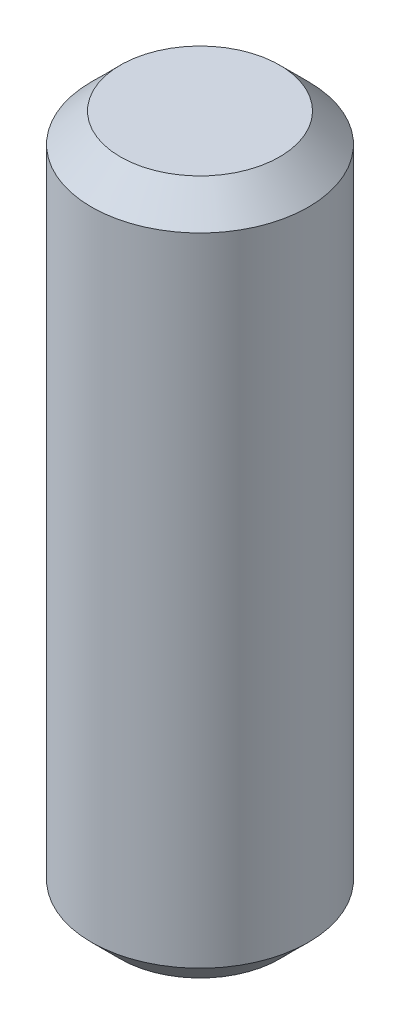
SolidWorks part; units mm, degrees
material "Plain Carbon Steel"
ref_plane "Front Plane" through (0, 0, 0) normal (0, 0, 1) x (1, 0, 0)
ref_plane "Top Plane" through (0, 0, 0) normal (0, 1, 0) x (1, 0, 0)
ref_plane "Right Plane" through (0, 0, 0) normal (1, 0, 0) x (0, 0, -1)
sketch "Sketch1" plane through (0, 0, 0) normal (0, 1, 0) x (1, 0, 0)
  circle A0 centre (0, 0) radius 7.5
  dimension "D1" = 15
extrude "Boss-Extrude1" add sketch "Sketch1" along normal blind 48
chamfer "Chamfer1" distance 2 angle 45 2 edges at (0, 0, 7.5) (0, 48, 7.5)
